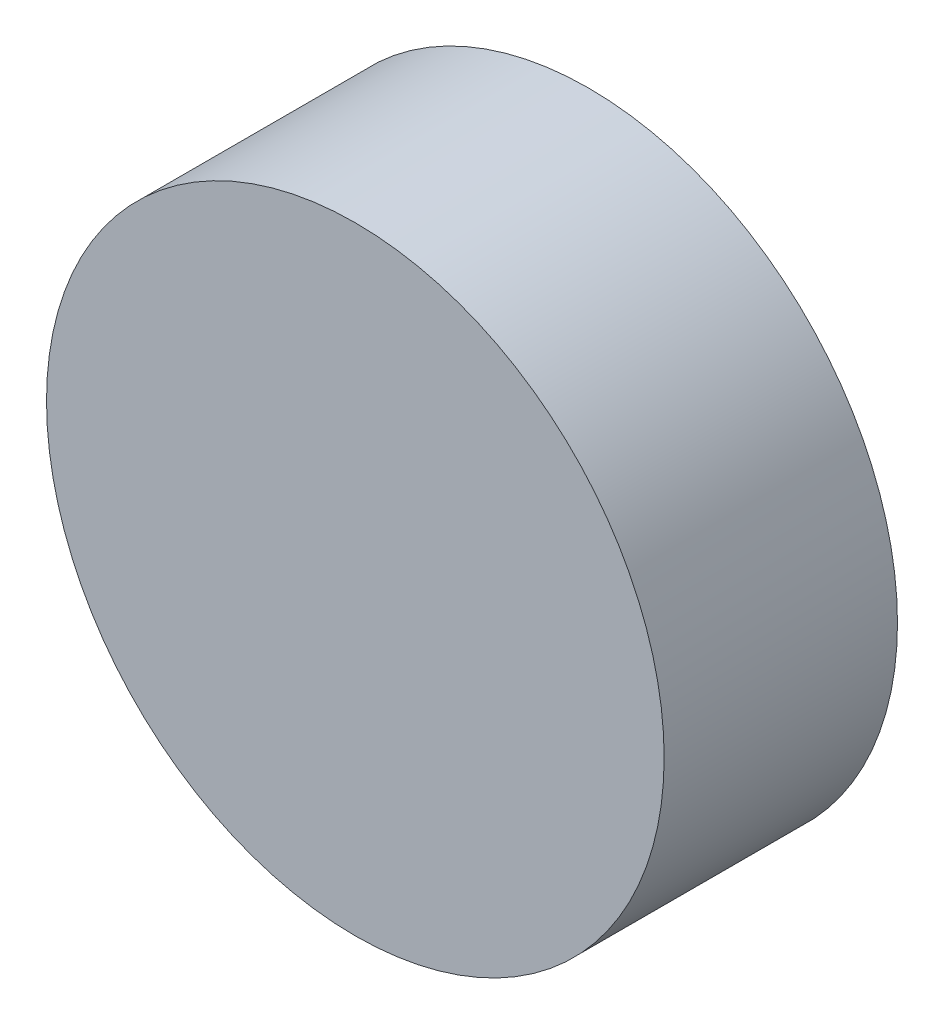
SolidWorks part; units mm, degrees
ref_plane "Front Plane" through (0, 0, 0) normal (0, 0, 1) x (1, 0, 0)
ref_plane "Top Plane" through (0, 0, 0) normal (0, 1, 0) x (1, 0, 0)
ref_plane "Right Plane" through (0, 0, 0) normal (1, 0, 0) x (0, 0, -1)
sketch "Sketch1" plane through (0, 0, 0) normal (0, 0, 1) x (1, 0, 0)
  circle A0 centre (0, 0) radius 2.25
  dimension "D1" = 4.5
extrude "Boss-Extrude1" add sketch "Sketch1" along normal blind 1.7
